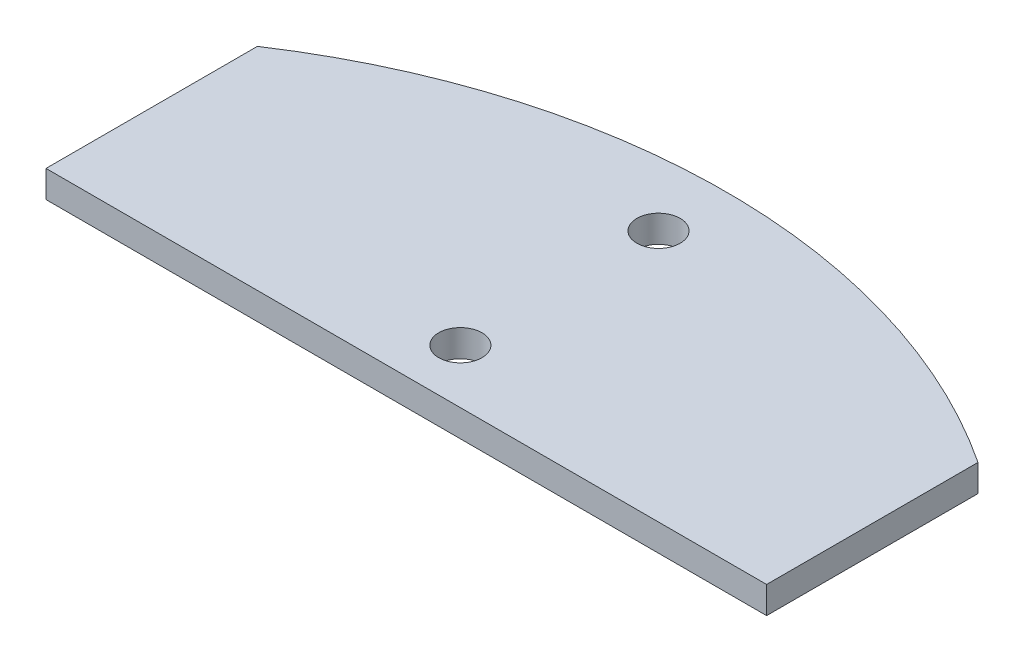
SolidWorks part; units mm, degrees
material "Acrylic (Medium-high impact)"
ref_plane "Front Plane" through (0, 0, 0) normal (0, 0, 1) x (1, 0, 0)
ref_plane "Top Plane" through (0, 0, 0) normal (0, 1, 0) x (1, 0, 0)
ref_plane "Right Plane" through (0, 0, 0) normal (1, 0, 0) x (0, 0, -1)
sketch "Sketch1" plane through (0, 0, 0) normal (0, 1, 0) x (1, 0, 0)
  line L0 (0, -85) -> (-32.4891, -64.8129) construction
  line L1 (0, -85) -> (0, 0) construction
  arc A0 (36.5434, -62.6165) -> (-36.5434, -62.6165) centre (0, 0) ccw
  arc A1 (30.0898, -61.3851) -> (-30.0898, -61.3851) centre (0, -85) ccw
  arc A2 (-30.0898, -61.3851) -> (-36.5434, -62.6165) centre (-34.0231, -58.2982) cw
  arc A3 (36.5434, -62.6165) -> (30.0898, -61.3851) centre (34.0231, -58.2982) cw
  dimension "D1" = 145
  dimension "D2" = 76.5
  dimension "D4" = 5
  dimension "D3" = 85
extrude "Boss-Extrude1" add sketch "Sketch1" along normal blind 3
sketch "Sketch11" plane through (0, 0, 0) normal (0, -1, 0) x (1, 0, 0)
  line L1 (40, -37) -> (-40, -37)
  line L2 (40, -37) -> (40, -77)
  line L3 (40, -77) -> (-40, -77)
  line L4 (-40, -37) -> (-40, -77)
  line L5 (40, -37) -> (-40, -77) construction
  line L6 (40, -77) -> (-40, -37) construction
  arc A0 (7.8724, -66.4231) -> (-7.8724, -66.4231) centre (0, -65) ccw construction
  point P0 (0, -57)
  dimension "D1" = 80
  dimension "D2" = 40
extrude "Cut-Extrude13" cut sketch "Sketch11" against normal through all flip side to cut
sketch "Sketch12" plane through (0, 0, 0) normal (0, -1, 0) x (1, 0, 0)
  circle A0 centre (0, -65) radius 2.4
  circle A1 centre (0, -43) radius 2.4
  dimension "D1" = 4.8
  dimension "D2" = 22
extrude "Cut-Extrude15" cut sketch "Sketch12" against normal through all
equation "\"smallPulleyTeeth\"= 30"
equation "\"largePulleyTeeth\"= 30"
equation "\"eighthThick\"= 3.0mm"
equation "\"sixteenthThick\" = 1.7mm"
equation "\"quarterThick\"=6.0mm"
equation "\"OD\" = 145mm"
equation "\"puckAngle\" = 60.5deg"
equation "\"D1@Sketch1\"=\"OD\""
equation "\"puckDiam\" = 76.5mm"
equation "\"D2@Sketch1\"=\"puckDiam\""
equation "\"D1@Boss-Extrude1\"=\"eighthThick\""
equation "\"axlePress\" = 5.9mm"
equation "\"press\" = 0.2mm"
equation "\"wheelClear\" = 0.3mm"
equation "\"10-32clear\" = 4.8mm"
equation "\"6-32clear\" = 3.3mm"
equation "\"8-32clear\" = 4.0mm"
equation "\"wheelHeight\" = 22mm"
equation "\"wheelWell\" = 65mm"
equation "\"D1@Sketch3\"=\"wheelWell\""
equation "\"puckDist\" = 85mm"
equation "\"scoopFillet\" = 5mm"
equation "\"4-40clear\" = 3.0mm"
equation "\"D3@Sketch1\"=\"puckDist\""
equation "\"D4@Sketch1\"=\"scoopFillet\""
equation "\"D3@Sketch9\"=\"6-32clear\""
equation "\"D1@Sketch12\"=\"10-32clear\""
